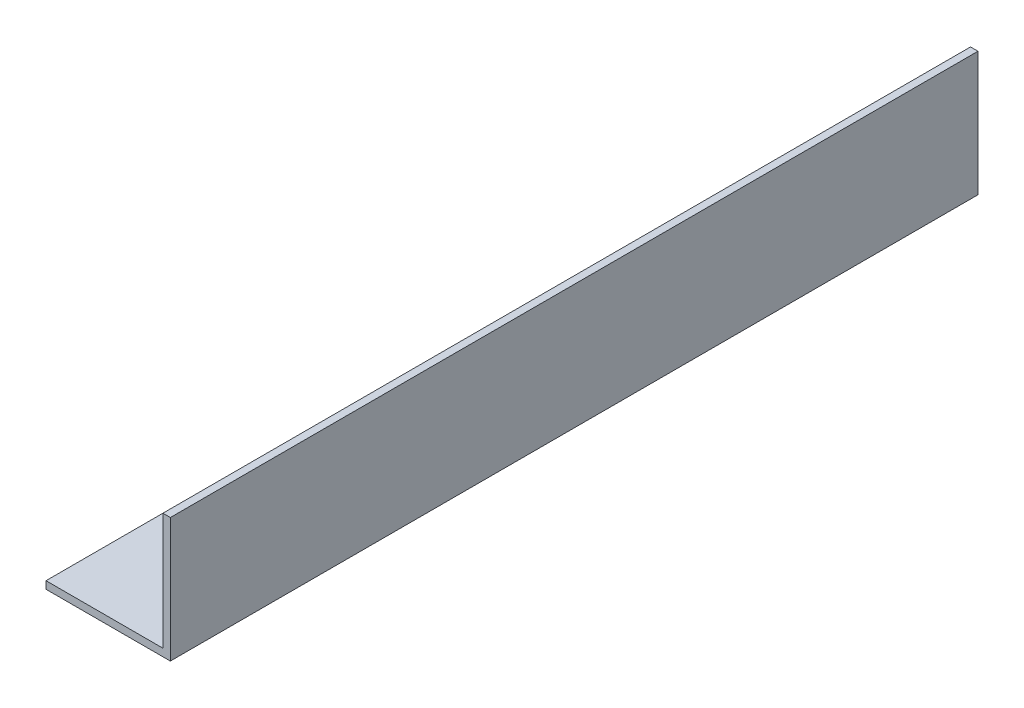
SolidWorks part; units mm, degrees
ref_plane "Front Plane" through (0, 0, 0) normal (0, 0, 1) x (1, 0, 0)
ref_plane "Top Plane" through (0, 0, 0) normal (0, 1, 0) x (1, 0, 0)
ref_plane "Right Plane" through (0, 0, 0) normal (1, 0, 0) x (0, 0, -1)
sketch "Sketch1" plane through (0, 0, 0) normal (0, 0, 1) x (1, 0, 0)
  line L0 (-50, 0) -> (0, 0)
  line L1 (0, 0) -> (0, 50)
  line L2 (0, 50) -> (-3, 50)
  line L3 (-3, 50) -> (-3, 3)
  line L4 (-3, 3) -> (-50, 3)
  line L5 (-50, 0) -> (-50, 3)
  line L6 (-1.5, 50) -> (0, 50) construction
  line L7 (-50, 1.5) -> (-50, 0) construction
  dimension "Vert" = 50
  dimension "Horz" = 50
  dimension "Thickness" = 3
sketch "Sketch2" plane through (0, 0, 0) normal (1, 0, 0) x (0, 0, -1)
  line L0 (-304.8, 0) -> (304.8, 0) construction
  point P0 (-292.608, 0)
  point P4 (0, 0)
  point P5 (292.608, 0)
  dimension "Length" = 609.6
  dimension "D1" = 12.192
  dimension "D2" = 12.192
sketch "Sketch3" plane through (0, 0, 0) normal (0, 0, 1) x (1, 0, 0)
  line L0 (-50, 0) -> (0, 0) construction
  line L1 (0, 0) -> (0, 50) construction
  line L2 (0, 50) -> (-3, 50) construction
  line L3 (-3, 50) -> (-3, 3) construction
  line L4 (-3, 3) -> (-50, 3) construction
  line L5 (-50, 0) -> (-50, 3) construction
  line L6 (-50, 0) -> (0, 0)
  line L7 (0, 0) -> (0, 50)
  line L8 (0, 50) -> (-3, 50)
  line L9 (-3, 50) -> (-3, 3)
  line L10 (-3, 3) -> (-50, 3)
  line L11 (-50, 0) -> (-50, 3)
extrude "Boss-Extrude1" add sketch "Sketch3" along normal blind 20 and the other way up to vertex (304.8 mm away) other way up to point (0, 0, -304.8)
sketch "Sketch4" plane through (0, 0, 0) normal (0, 1, 0) x (1, 0, 0)
  line L0 (-26.5, -20) -> (-26.5, 304.8) construction
  line L1 (-3, -20) -> (-50, -20) construction
  line L2 (-3, 304.8) -> (-50, 304.8) construction
  line L3 (-50, 142.4) -> (-3, 142.4) construction
  line L4 (-50, 304.8) -> (-50, -20) construction
  line L5 (-3, 304.8) -> (-3, -20) construction
  circle A0 centre (-37, 151.19) radius 2.585
  circle A1 centre (-16, 151.19) radius 2.585
  circle A2 centre (-37, 179.19) radius 2.585
  circle A3 centre (-16, 179.19) radius 2.585
  circle A4 centre (-37, 105.61) radius 2.585
  circle A5 centre (-16, 105.61) radius 2.585
  circle A6 centre (-16, 133.61) radius 2.585
  circle A7 centre (-37, 133.61) radius 2.585
  dimension "D1" = 5.17
  dimension "D3" = 5.17
  dimension "D2" = 10.5
  dimension "D4" = 28
  dimension "D5" = 8.79
extrude "Cut-Extrude1" cut sketch "Sketch4" along normal through all
equation "\"D1@Sketch2\"=\"Length@Sketch2\"*.02"
equation "\"D2@Sketch2\"=\"D1@Sketch2\""
